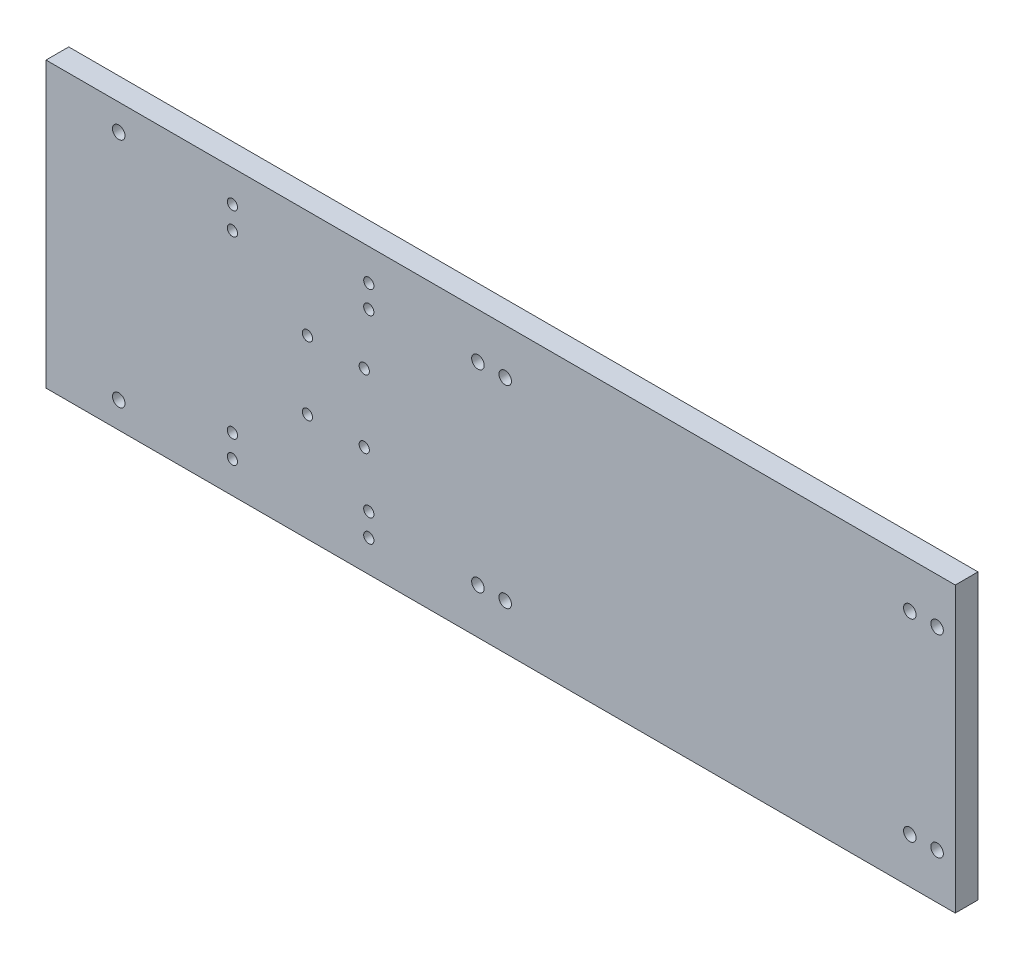
SolidWorks part; units mm, degrees
ref_plane "Front Plane" through (0, 0, 0) normal (0, 0, 1) x (1, 0, 0)
ref_plane "Top Plane" through (0, 0, 0) normal (0, 1, 0) x (1, 0, 0)
ref_plane "Right Plane" through (0, 0, 0) normal (1, 0, 0) x (0, 0, -1)
sketch "Sketch1" plane through (0, 0, 0) normal (0, 0, 1) x (1, 0, 0)
  line L0 (-60, 15) -> (-85, 15) construction
  line L1 (-200, -62.5) -> (200, -62.5)
  line L2 (-200, -62.5) -> (-200, 62.5)
  line L3 (-200, 62.5) -> (200, 62.5)
  line L4 (200, -62.5) -> (200, 62.5)
  line L5 (-200, -62.5) -> (200, 62.5) construction
  line L6 (-200, 62.5) -> (200, -62.5) construction
  line L7 (-85, 15) -> (-85, -15) construction
  line L8 (-85, -15) -> (-60, -15) construction
  line L9 (-60, -15) -> (-60, 15) construction
  line L10 (2, 42.5) -> (-10, 42.5) construction
  line L11 (-10, 42.5) -> (-10, -42.5) construction
  line L12 (-10, -42.5) -> (2, -42.5) construction
  line L13 (2, -42.5) -> (2, 42.5) construction
  line L14 (192, 42.5) -> (180, 42.5) construction
  line L15 (180, 42.5) -> (180, -42.5) construction
  line L16 (180, -42.5) -> (192, -42.5) construction
  line L17 (192, -42.5) -> (192, 42.5) construction
  line L18 (-168, 51) -> (-168, -51) construction
  line L19 (180, 0) -> (2, 0) construction
  line L20 (-60, 0) -> (-10, 0) construction
  line L21 (-58, 38.5) -> (-118, 38.5) construction
  line L22 (-118, 38.5) -> (-118, -38.5) construction
  line L23 (-118, -38.5) -> (-58, -38.5) construction
  line L24 (-58, -38.5) -> (-58, 38.5) construction
  line L25 (-168, 0) -> (-118, 0) construction
  line L26 (-58, 38.5) -> (-58, 48.5) construction
  line L27 (-58, 48.5) -> (-118, 48.5) construction
  line L28 (-118, 48.5) -> (-118, 38.5) construction
  line L29 (-58, -38.5) -> (-58, -48.5) construction
  line L30 (-58, -48.5) -> (-118, -48.5) construction
  line L31 (-118, -48.5) -> (-118, -38.5) construction
  point P0 (-60, 15)
  point P5 (-168, -51)
  point P6 (192, 42.5)
  point P7 (180, 42.5)
  point P9 (192, -42.5)
  point P10 (180, -42.5)
  point P11 (2, 42.5)
  point P13 (2, -42.5)
  point P14 (-10, -42.5)
  point P15 (-85, 15)
  point P19 (-85, -15)
  point P20 (-60, -15)
  point P21 (-168, 51)
  point P43 (-58, 38.5)
  point P44 (-118, 38.5)
  point P45 (-118, -38.5)
  point P46 (-58, -38.5)
  point P55 (-10, 42.5)
  point P57 (-58, 48.5)
  point P58 (-118, 48.5)
  point P59 (-58, -48.5)
  point P60 (-118, -48.5)
  dimension "D3" = 85
  dimension "D4" = 12
  dimension "D5" = 12
  dimension "D6" = 50
  dimension "D8" = 77
  dimension "D9" = 60
  dimension "D11" = 102
  dimension "D12" = 178
  dimension "D13" = 25
  dimension "D14" = 8
  dimension "D15" = 10
  dimension "D16" = 10
  dimension "D19" = 125
  dimension "D20" = 400
  dimension "D21" = 32
  dimension "D7" = 30
  dimension "D10" = 50
extrude "Boss-Extrude1" add sketch "Sketch1" along normal blind 10
hole_wizard "Taladro de margen para M51" positions "Croquis7" profile "Croquis6" hole size "M5" standard "IS" end condition through all
sketch "Croquis7" plane through (0, 0, 0) normal (0, 0, -1) x (-1, 0, 0)
  point P0 (-192, 42.5)
  point P3 (-180, 42.5)
  point P6 (-192, -42.5)
  point P9 (-180, -42.5)
  point P12 (-2, 42.5)
  point P15 (10, 42.5)
  point P18 (-2, -42.5)
  point P21 (10, -42.5)
  point P24 (168, 51)
  point P27 (168, -51)
sketch "Croquis6" plane through (192, 42.5, 0) normal (1, 0, 0) x (0, 1, 0)
  line L0 (0, 0) -> (0, 10)
  line L1 (0, 10) -> (2.75, 10)
  line L2 (2.75, 10) -> (2.75, 0)
  line L5 (2.75, 0) -> (0, 0)
  line L11 (0, -6.35) -> (0, 107.95) construction
  dimension "Diámetro de taladro hasta el siguiente" = 5.5
  dimension "Profundidad de taladro hasta el siguiente" = 10
hole_wizard "Taladro de margen para M41" positions "Croquis8" profile "Croquis9" hole size "M4" standard "IS" end condition through all
sketch "Croquis8" plane through (0, 0, 0) normal (0, 0, -1) x (-1, 0, 0)
  point P0 (58, 38.5)
  point P3 (118, 38.5)
  point P6 (118, -38.5)
  point P9 (58, -38.5)
  point P12 (60, -15)
  point P15 (85, -15)
  point P18 (85, 15)
  point P21 (60, 15)
  point P24 (58, -48.5)
  point P27 (118, -48.5)
  point P30 (58, 48.5)
  point P33 (118, 48.5)
sketch "Croquis9" plane through (-58, 38.5, 0) normal (1, 0, 0) x (0, 1, 0)
  line L0 (0, 0) -> (0, 10)
  line L1 (0, 10) -> (2.25, 10)
  line L2 (2.25, 10) -> (2.25, 0)
  line L5 (2.25, 0) -> (0, 0)
  line L11 (0, -6.35) -> (0, 107.95) construction
  dimension "Diámetro de taladro hasta el siguiente" = 4.5
  dimension "Profundidad de taladro hasta el siguiente" = 10
